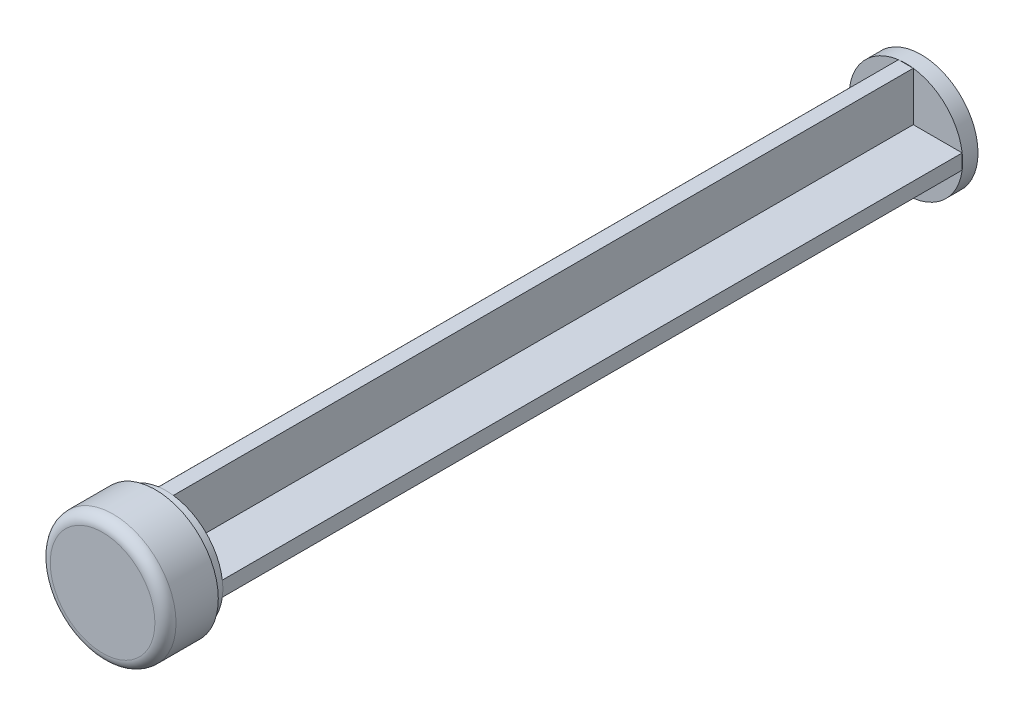
SolidWorks part; units mm, degrees
ref_plane "Alzado" through (0, 0, 0) normal (0, 0, 1) x (1, 0, 0)
ref_plane "Planta" through (0, 0, 0) normal (0, 1, 0) x (1, 0, 0)
ref_plane "Vista lateral" through (0, 0, 0) normal (1, 0, 0) x (0, 0, -1)
sketch "Croquis1" plane through (0, 0, 0) normal (0, 0, 1) x (1, 0, 0)
  circle A0 centre (0, 0) radius 5.95
  dimension "D1" = 11.9
extrude "Saliente-Extruir1" add sketch "Croquis1" along normal blind 5
sketch "Croquis2" plane through (0, 0, 0) normal (0, 0, -1) x (-1, 0, 0)
  circle A0 centre (0, 0) radius 5.375
  dimension "D1" = 10.75
extrude "Saliente-Extruir2" add sketch "Croquis2" along normal blind 1
sketch "Croquis4" plane through (0, 0, -1) normal (0, 0, -1) x (-1, 0, 0)
  line L1 (-0.7, 5.3292) -> (0.7, 5.3292)
  line L2 (-0.7, 5.3292) -> (-0.7, -5.3292)
  line L3 (-0.7, -5.3292) -> (0.7, -5.3292)
  line L4 (0.7, 5.3292) -> (0.7, -5.3292)
  line L5 (-0.7, 5.3292) -> (0.7, -5.3292) construction
  line L6 (-0.7, -5.3292) -> (0.7, 5.3292) construction
  line L7 (-5.3286, 0.705) -> (5.3286, 0.705)
  line L8 (-5.3286, 0.705) -> (-5.3286, -0.705)
  line L9 (-5.3286, -0.705) -> (5.3286, -0.705)
  line L10 (5.3286, 0.705) -> (5.3286, -0.705)
  line L11 (-5.3286, 0.705) -> (5.3286, -0.705) construction
  line L12 (-5.3286, -0.705) -> (5.3286, 0.705) construction
  circle A0 centre (0, 0) radius 5.375 construction
  circle A1 centre (0, 0) radius 5.375 construction
  point P0 (0, 0)
  point P8 (0, 0)
  dimension "D1" = 1.4
  dimension "D2" = 1.41
extrude "Saliente-Extruir3" add sketch "Croquis4" along normal blind 70 contours L2 L7 L4 L1 | L2 L9 L4 L7 | L9 L2 L3 L4 | L8 L9 L2 L7 | L10 L7 L4 L9
fillet "Redondeo1" radius 1 1 edges at (5.95, 0, 5)
sketch "Croquis5" plane through (0, 0, -71) normal (0, 0, -1) x (-1, 0, 0)
  circle A0 centre (0, 0) radius 5.375
extrude "Saliente-Extruir4" add sketch "Croquis5" along normal blind 1.45
